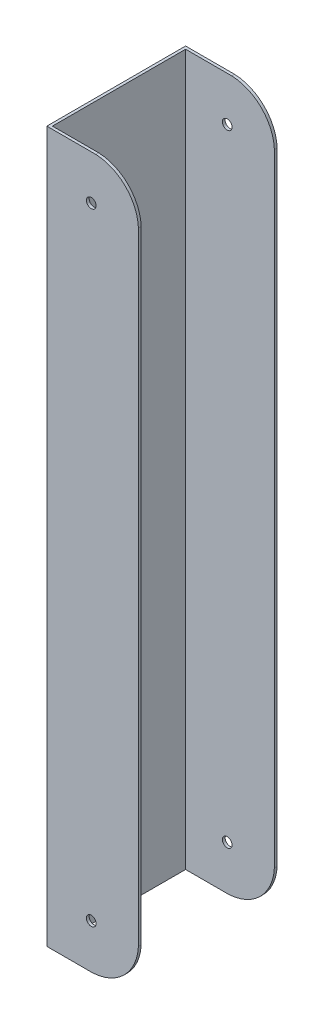
SolidWorks part; units mm, degrees
ref_plane "Front Plane" through (0, 0, 0) normal (0, 0, 1) x (1, 0, 0)
ref_plane "Top Plane" through (0, 0, 0) normal (0, 1, 0) x (1, 0, 0)
ref_plane "Right Plane" through (0, 0, 0) normal (1, 0, 0) x (0, 0, -1)
sketch "Sketch1" plane through (0, 0, 0) normal (0, 1, 0) x (1, 0, 0)
  line L0 (0, 0) -> (-52.3875, 0)
  line L1 (-52.3875, 0) -> (-52.3875, 79.375)
  line L2 (-52.3875, 79.375) -> (0, 79.375)
  line L3 (0, 79.375) -> (0, 77.7875)
  line L4 (0, 77.7875) -> (-50.8, 77.7875)
  line L5 (-50.8, 77.7875) -> (-50.8, 1.5875)
  line L6 (-50.8, 1.5875) -> (0, 1.5875)
  line L7 (0, 1.5875) -> (0, 0)
  dimension "D1" = 76.2
  dimension "D2" = 1.5875
  dimension "D3" = 1.5875
  dimension "D4" = 1.5875
  dimension "D5" = 50.8
extrude "Boss-Extrude1" add sketch "Sketch1" along normal blind 406.4
sketch "Sketch2" plane through (0, 0, 0) normal (0, 0, 1) x (1, 0, 0)
  line L1 (-52.3875, 406.4) -> (0, 406.4) construction
  line L2 (0, 406.4) -> (0, 0) construction
  line L3 (-25.2913, 406.4161) -> (0, 406.4)
  line L4 (0, 406.4) -> (0, 382.0112)
  line L5 (-52.3875, 0) -> (0, 0) construction
  line L6 (-26.1937, 0) -> (0, 0)
  line L7 (0, 0) -> (0, 29.1018)
  arc A0 (-26.1937, 406.4) -> (0, 382.0112) centre (-25.2913, 381.1087) cw
  arc A1 (-26.1937, 0) -> (0, 29.1018) centre (-27.6478, 27.6478) ccw
  line M1 (-52.3875, 0) -> (0, 0)
  line M2 (0, 0) -> (0, 406.4)
  line M3 (0, 406.4) -> (-52.3875, 406.4)
extrude "Cut-Extrude1" cut sketch "Sketch2" against normal blind 406.4 contours A1 M1 M2 | A0 M3 M2
sketch "Sketch3" plane through (0, 0, 0) normal (0, 0, 1) x (1, 0, 0)
  line L0 (-52.3875, 0) -> (-26.1937, 0) construction
  line L1 (-52.3875, 406.4) -> (-52.3875, 0) construction
  line L2 (-52.3875, 406.4) -> (-24.3888, 406.4) construction
  circle A0 centre (-26.9875, 381) radius 2.7781
  circle A1 centre (-26.9875, 25.4) radius 2.7781
  dimension "D1" = 5.5562
  dimension "D6" = 5.5562
  dimension "D2" = 25.4
  dimension "D3" = 25.4
  dimension "D4" = 25.4
  dimension "D5" = 25.4
extrude "Cut-Extrude2" cut sketch "Sketch3" against normal blind 406.4
